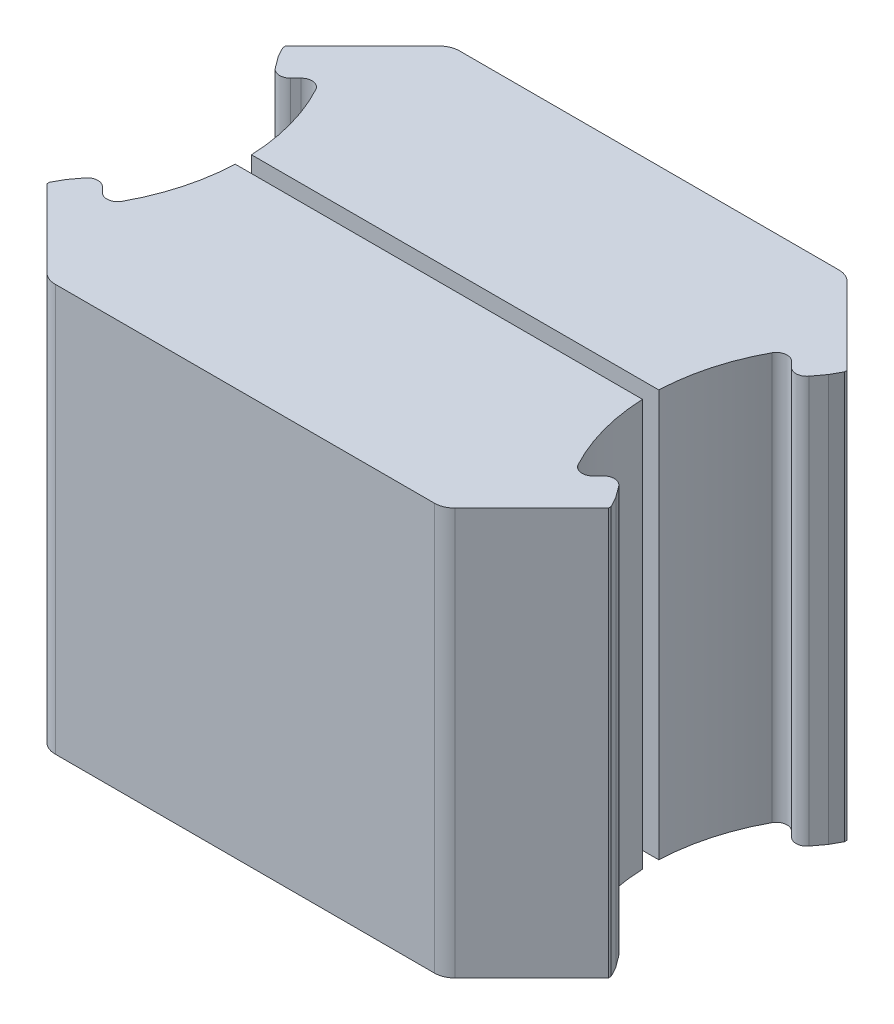
SolidWorks part; units mm, degrees
material "6061 Alloy"
ref_plane "Front Plane" through (0, 0, 0) normal (0, 0, 1) x (1, 0, 0)
ref_plane "Top Plane" through (0, 0, 0) normal (0, 1, 0) x (1, 0, 0)
ref_plane "Right Plane" through (0, 0, 0) normal (1, 0, 0) x (0, 0, -1)
sketch "Sketch2" plane through (0, 0, 0) normal (0, 1, 0) x (1, 0, 0)
  line L0 (-10.0707, -4.0276) -> (-4.41, -9.6883)
  line L1 (-3.3493, -10.1276) -> (24.608, -10.1276)
  line L2 (25.6687, -9.6883) -> (31.3293, -4.0276)
  line L3 (31.3293, -4.0276) -> (31.3293, -3.8271)
  line L4 (31.3293, -3.8271) -> (30.9151, -3.0684)
  line L5 (30.9151, -3.0684) -> (30.3063, -2.2471)
  line L6 (29.0979, -2.1578) -> (28.7056, -2.5501)
  line L7 (25.6414, 4.1724) -> (-4.3827, 4.1724)
  line L8 (-7.4469, -2.5501) -> (-7.8392, -2.1578)
  line L9 (-9.0476, -2.2471) -> (-9.5186, -2.8826)
  line L10 (-9.5186, -2.8826) -> (-9.6564, -3.0684)
  line L11 (-9.6564, -3.0684) -> (-9.8635, -3.4478)
  line L12 (-9.8635, -3.4478) -> (-10.0707, -3.8271)
  line L13 (-10.0707, -3.8271) -> (-10.0707, -4.0276)
  line L14 (31.3293, 13.5724) -> (25.6687, 19.233)
  line L15 (24.608, 19.6724) -> (-3.3493, 19.6724)
  line L16 (-4.41, 19.233) -> (-10.0707, 13.5724)
  line L17 (-10.0707, 13.5724) -> (-10.0707, 13.3718)
  line L18 (-10.0707, 13.3718) -> (-9.6564, 12.6132)
  line L19 (-9.6564, 12.6132) -> (-9.0476, 11.7919)
  line L20 (-7.8392, 11.7025) -> (-7.4469, 12.0949)
  line L21 (-4.3827, 5.3724) -> (25.6414, 5.3724)
  line L22 (28.7056, 12.0949) -> (29.0979, 11.7025)
  line L23 (30.3063, 11.7919) -> (30.7773, 12.4273)
  line L24 (30.7773, 12.4273) -> (30.9151, 12.6132)
  line L25 (30.9151, 12.6132) -> (31.1222, 12.9925)
  line L26 (31.1222, 12.9925) -> (31.3293, 13.3718)
  line L27 (31.3293, 13.3718) -> (31.3293, 13.5724)
  arc A0 (-4.41, -9.6883) -> (-3.3493, -10.1276) centre (-3.3493, -8.6276) ccw
  arc A1 (24.608, -10.1276) -> (25.6687, -9.6883) centre (24.608, -8.6276) ccw
  arc A2 (30.3063, -2.2471) -> (29.0979, -2.1578) centre (29.6636, -2.7235) ccw
  arc A3 (27.4363, -2.3651) -> (28.7056, -2.5501) centre (28.1399, -1.9845) ccw
  arc A4 (25.6414, 4.1724) -> (27.4363, -2.3651) centre (40.6293, 4.7724) ccw
  arc A5 (-6.1776, -2.3651) -> (-4.3827, 4.1724) centre (-19.3707, 4.7724) ccw
  arc A6 (-7.4469, -2.5501) -> (-6.1776, -2.3651) centre (-6.8812, -1.9845) ccw
  arc A7 (-7.8392, -2.1578) -> (-9.0476, -2.2471) centre (-8.4049, -2.7235) ccw
  arc A8 (25.6687, 19.233) -> (24.608, 19.6724) centre (24.608, 18.1724) ccw
  arc A9 (-3.3493, 19.6724) -> (-4.41, 19.233) centre (-3.3493, 18.1724) ccw
  arc A10 (-9.0476, 11.7919) -> (-7.8392, 11.7025) centre (-8.4049, 12.2682) ccw
  arc A11 (-6.1776, 11.9098) -> (-7.4469, 12.0949) centre (-6.8812, 11.5292) ccw
  arc A12 (-4.3827, 5.3724) -> (-6.1776, 11.9098) centre (-19.3707, 4.7724) ccw
  arc A13 (27.4363, 11.9098) -> (25.6414, 5.3724) centre (40.6293, 4.7724) ccw
  arc A14 (28.7056, 12.0949) -> (27.4363, 11.9098) centre (28.1399, 11.5292) ccw
  arc A15 (29.0979, 11.7025) -> (30.3063, 11.7919) centre (29.6636, 12.2682) ccw
extrude "Boss-Extrude1" add sketch "Sketch2" along normal blind 30
